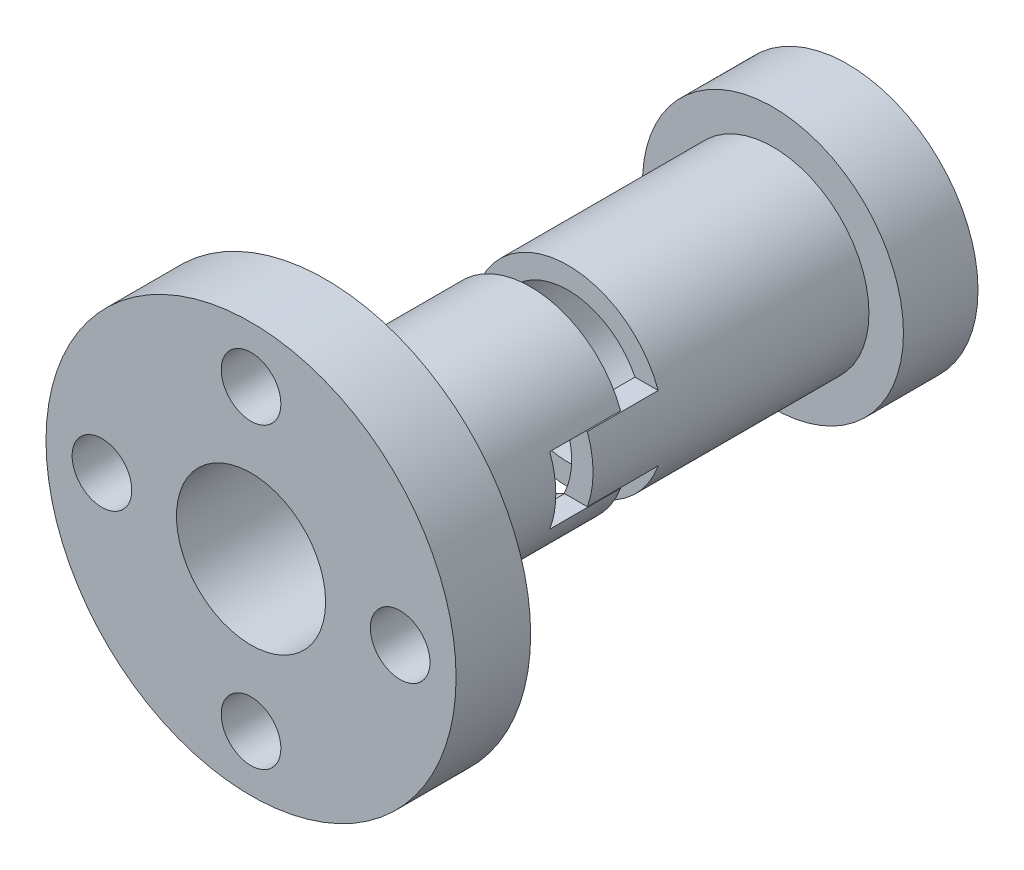
SolidWorks part; units mm, degrees
material "Bronce comercial, UNS C22000 (90-10 bronce)"
ref_plane "Front Plane" through (0, 0, 0) normal (0, 0, 1) x (1, 0, 0)
ref_plane "Top Plane" through (0, 0, 0) normal (0, 1, 0) x (1, 0, 0)
ref_plane "Right Plane" through (0, 0, 0) normal (1, 0, 0) x (0, 0, -1)
sketch "Croquis1" plane through (0, 0, 0) normal (1, 0, 0) x (0, 0, -1)
  line L0 (0, 4) -> (0, 11)
  line L1 (0, 11) -> (4, 11)
  line L2 (4, 11) -> (4, 5.15)
  line L3 (4, 5.15) -> (28, 5.15)
  line L5 (32, 4) -> (0, 4)
  line L6 (0, 0) -> (15, 0) construction
  line L7 (28, 5.15) -> (28, 7)
  line L8 (28, 7) -> (32, 7)
  line L9 (32, 7) -> (32, 4)
  dimension "D1" = 4
  dimension "D2" = 11
  dimension "D3" = 5.15
  dimension "D4" = 4
  dimension "D5" = 32
  dimension "D6" = 4
  dimension "D7" = 7
revolve "Revolución1" add sketch "Croquis1" angle 360 about L6
hole_wizard "Taladro de margen para M31" positions "Croquis2" profile "Croquis3" hole size "M3" standard "ISO"
sketch "Croquis2" plane through (0, 0, 0) normal (0, 0, 1) x (1, 0, 0)
  point P0 (8, 0)
  dimension "D1" = 8
sketch "Croquis3" plane through (8, 0, 0) normal (1, 0, 0) x (0, -1, 0)
  line L0 (0, 0) -> (0, 8.6)
  line L1 (0, 8.6) -> (1.6, 7)
  line L2 (1.6, 7) -> (1.6, 0)
  line L5 (1.6, 0) -> (0, 0)
  line L10 (0, 8.6) -> (-1.6, 7) construction
  line L11 (0, -6.35) -> (0, 107.95) construction
  dimension "Diámetro de taladro" = 3.2
  dimension "Profundidad de taladro" = 7
  dimension "Ángulo de perforador" = 90
pattern_circular "MatrizC1" count 4 over 360 about axis through (0, 0, 0) along (0, 0, 1) of "Taladro de margen para M31"
sketch "Croquis4" plane through (0, 0, 0) normal (1, 0, 0) x (0, 0, -1)
  line L1 (11.2, -1.8) -> (15, -1.8)
  line L2 (11.2, -1.8) -> (11.2, 1.8)
  line L3 (11.2, 1.8) -> (15, 1.8)
  line L7 (15, 1.8) -> (15, 5.15)
  line L8 (28, 5.15) -> (4, 5.15) construction
  line L9 (15, 5.15) -> (17, 5.15)
  line L10 (17, 5.15) -> (17, 1.75)
  line L11 (17, 1.75) -> (13.2, 1.75)
  line L12 (13.2, 1.75) -> (13.2, -1.75)
  line L13 (13.2, -1.75) -> (17, -1.75)
  line L14 (17, -1.75) -> (17, -5.15)
  line L15 (17, -5.15) -> (15, -5.15)
  line L16 (15, -5.15) -> (15, -1.8)
  point P0 (11.2, 0)
  point P5 (13.2, 0)
  dimension "D3" = 10.3
  dimension "D1" = 3.6
  dimension "D2" = 3.8
  dimension "D4" = 2
  dimension "D5" = 3.5
  dimension "D6" = 15
  dimension "D7" = 2
extrude "Cortar-Extruir1" cut sketch "Croquis4" against normal through all and the other way through all
